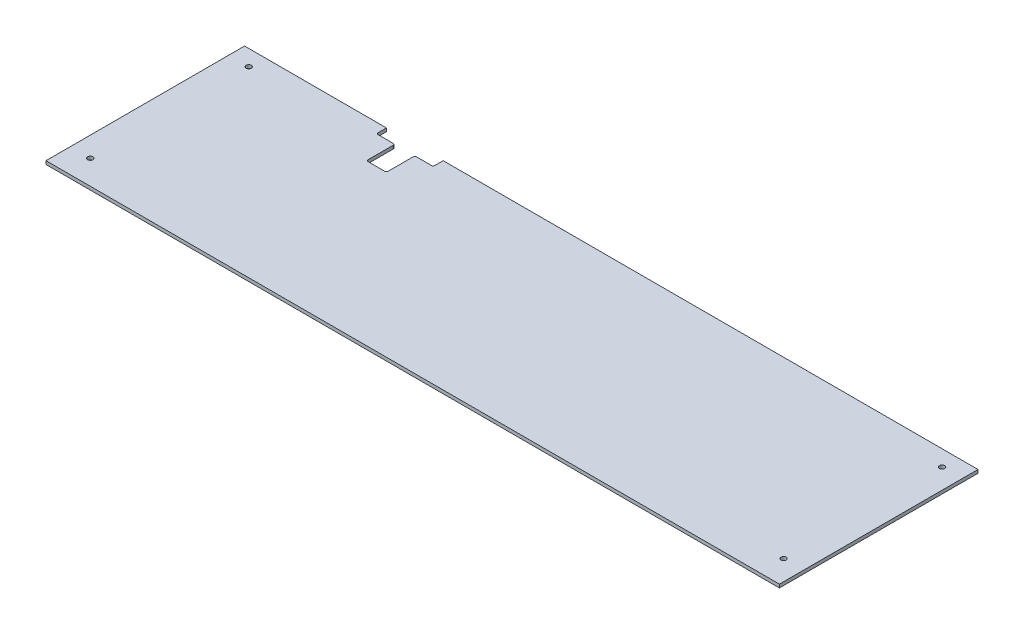
SolidWorks part; units mm, degrees
ref_plane "Alzado" through (0, 0, 0) normal (0, 0, 1) x (1, 0, 0)
ref_plane "Planta" through (0, 0, 0) normal (0, 1, 0) x (1, 0, 0)
ref_plane "Vista lateral" through (0, 0, 0) normal (1, 0, 0) x (0, 0, -1)
sketch "Croquis1" plane through (0, 0, 0) normal (0, 1, 0) x (1, 0, 0)
  line L0 (220.25, 120) -> (220.25, 0) construction
  line L1 (0, 0) -> (440.5, 0)
  line L2 (0, 0) -> (0, 120)
  line L3 (0, 120) -> (440.5, 120)
  line L4 (440.5, 0) -> (440.5, 120)
  line L5 (0, 60) -> (440.5, 60) construction
  circle A0 centre (12.5, 15) radius 1.55
  circle A1 centre (12.5, 110) radius 1.55
  circle A2 centre (428, 15) radius 1.55
  circle A3 centre (428, 110) radius 1.55
  dimension "D3" = 3.1
  dimension "D1" = 120
  dimension "D2" = 440.5
  dimension "D4" = 15
  dimension "D5" = 12.5
  dimension "D6" = 12.5
  dimension "D7" = 10
extrude "Saliente-Extruir1" add sketch "Croquis1" along normal blind 2
sketch "Croquis2" plane through (0, 0, 0) normal (0, -1, 0) x (1, 0, 0)
  line L0 (440, -0.5) -> (0.5, -0.5)
  line L1 (0.5, -0.5) -> (0.5, -119.5)
  line L2 (0.5, -119.5) -> (440, -119.5)
  line L3 (440, -119.5) -> (440, -0.5)
  line L4 (0, 0) -> (0, -120)
  line L5 (0, -120) -> (440.5, -120)
  line L6 (440.5, -120) -> (440.5, 0)
  line L7 (440.5, 0) -> (0, 0)
  line L8 (0, 0) -> (0, -120)
  line L9 (0, -120) -> (440.5, -120)
  line L10 (440.5, -120) -> (440.5, 0)
  line L11 (440.5, 0) -> (0, 0)
  dimension "D1" = 0
  dimension "D2" = 0.5
extrude "Cortar-Extruir1" cut sketch "Croquis2" against normal up to surface (2 mm away) up to face at (220.25, 2, -60)
sketch "Croquis3" plane through (0, 0, 0) normal (0, -1, 0) x (1, 0, 0)
  line L0 (0.5, -119.5) -> (440, -119.5) construction
  line L1 (85.5, -119.5) -> (119.5, -119.5)
  line L2 (85.5, -119.5) -> (85.5, -113.5)
  line L3 (85.5, -113.5) -> (96.5, -113.5)
  line L4 (119.5, -119.5) -> (119.5, -113.5)
  line L5 (108.5, -113.5) -> (119.5, -113.5)
  line L7 (96.5, -113.5) -> (96.5, -96.5)
  line L8 (96.5, -96.5) -> (108.5, -96.5)
  line L9 (108.5, -113.5) -> (108.5, -96.5)
  dimension "D1" = 34
  dimension "D2" = 6
  dimension "D3" = 12
  dimension "D4" = 85
  dimension "D5" = 17
  dimension "12" = 11
extrude "Cortar-Extruir2" cut sketch "Croquis3" against normal up to surface (2 mm away) up to face at (428, 2, -111.55)
fillet "Redondeo1" radius 1 6 edges at (85.5, 1, -113.5) (119.5, 1, -113.5) (108.5, 1, -113.5) (96.5, 1, -113.5) (96.5, 1, -96.5) (108.5, 1, -96.5)
